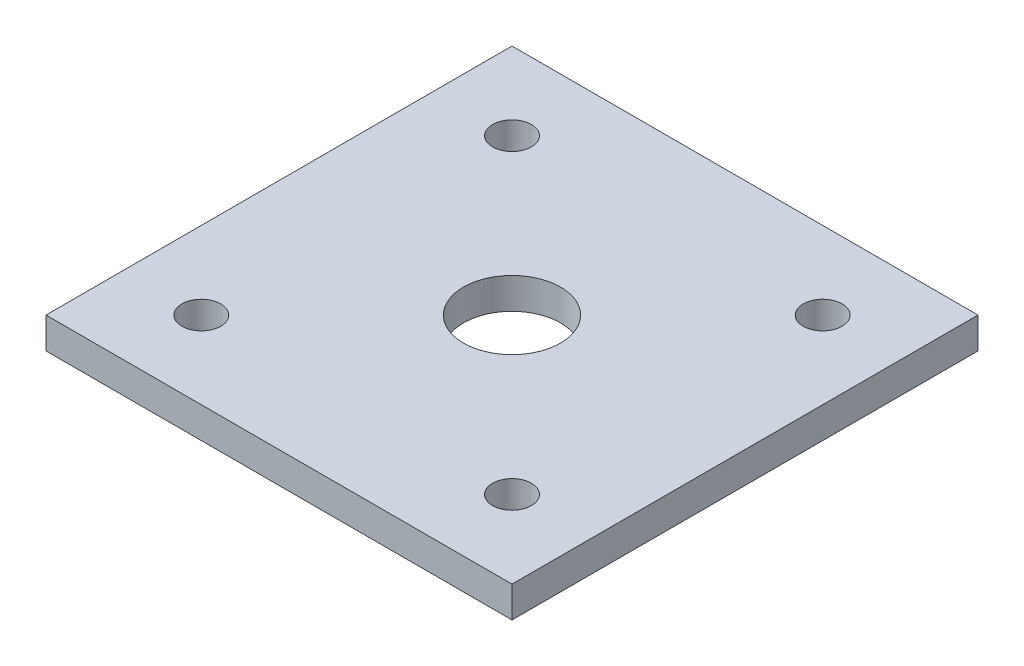
SolidWorks part; units mm, degrees
ref_plane "Front Plane" through (0, 0, 0) normal (0, 0, 1) x (1, 0, 0)
ref_plane "Top Plane" through (0, 0, 0) normal (0, 1, 0) x (1, 0, 0)
ref_plane "Right Plane" through (0, 0, 0) normal (1, 0, 0) x (0, 0, -1)
sketch "Sketch1" plane through (0, 0, 0) normal (0, 1, 0) x (1, 0, 0)
  line L1 (60, -60) -> (-60, -60)
  line L2 (60, -60) -> (60, 60)
  line L3 (60, 60) -> (-60, 60)
  line L4 (-60, -60) -> (-60, 60)
  line L5 (60, -60) -> (-60, 60) construction
  line L6 (60, 60) -> (-60, -60) construction
  point P0 (0, 0)
  dimension "D1" = 120
extrude "Boss-Extrude1" add sketch "Sketch1" along normal blind 8
sketch "Sketch2" plane through (0, 8, 0) normal (0, 1, 0) x (1, 0, 0)
  circle A0 centre (0, 0) radius 12.5
  dimension "D1" = 25
extrude "Cut-Extrude1" cut sketch "Sketch2" against normal through all
sketch "Sketch3" plane through (0, 8, 0) normal (0, 1, 0) x (1, 0, 0)
  line L1 (-60, 60) -> (-60, -60) construction
  line L2 (60, 60) -> (-60, 60) construction
  circle A0 centre (-40, 40) radius 5
  dimension "D1" = 10
  dimension "D2" = 20
  dimension "D3" = 20
extrude "Cut-Extrude2" cut sketch "Sketch3" against normal through all
pattern_linear "LPattern1" [suppressed] count 2 spacing 140 count 2 spacing 140
pattern_circular "CirPattern1" count 4 over 360 about axis through (0, 0, 0) along (0, 1, 0) of "Cut-Extrude2"
